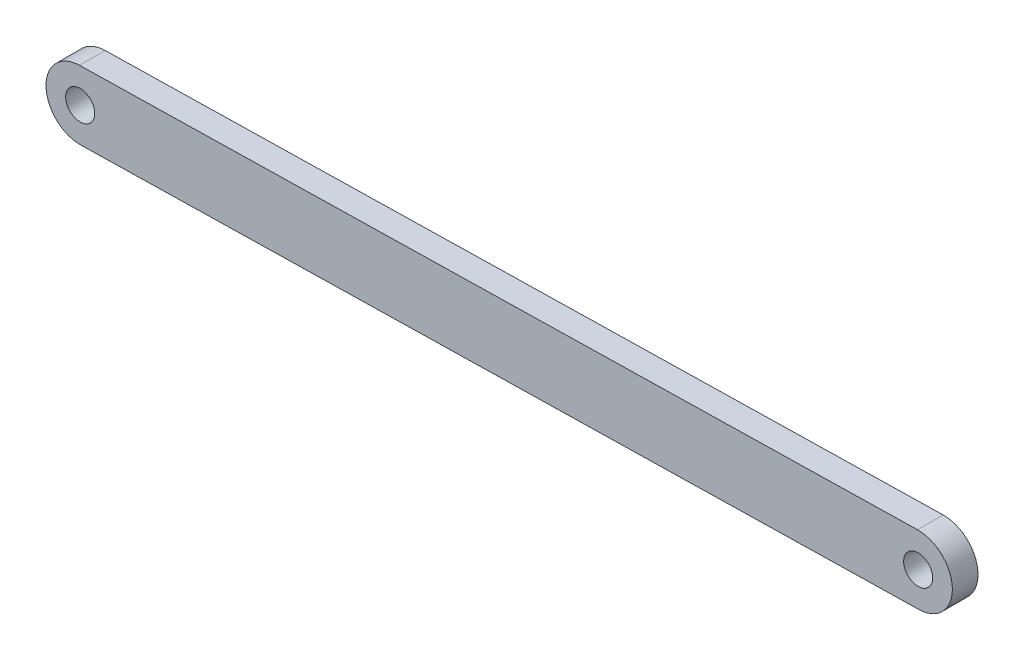
SolidWorks part; units mm, degrees
ref_plane "Front Plane" through (0, 0, 0) normal (0, 0, 1) x (1, 0, 0)
ref_plane "Top Plane" through (0, 0, 0) normal (0, 1, 0) x (1, 0, 0)
ref_plane "Right Plane" through (0, 0, 0) normal (1, 0, 0) x (0, 0, -1)
sketch "Sketch1" plane through (0, 0, 0) normal (0, 0, 1) x (1, 0, 0)
  line L0 (-12.0813, 0.8486) -> (85.9167, 2.8126) construction
  line L1 (-12.0813, 0.8486) -> (85.9167, 2.8126) construction
  line L2 (-12.1615, 4.8478) -> (85.8366, 6.8118)
  line L3 (-12.0012, -3.1505) -> (85.9969, -1.1866)
  circle A0 centre (-12.0813, 0.8486) radius 1.7
  circle A1 centre (85.9167, 2.8126) radius 1.7
  arc A2 (-12.1615, 4.8478) -> (-12.0012, -3.1505) centre (-12.0813, 0.8486) ccw
  arc A3 (85.9969, -1.1866) -> (85.8366, 6.8118) centre (85.9167, 2.8126) ccw
  circle A4 centre (-12.0813, 0.8486) radius 1.65 construction
  circle A5 centre (85.9167, 2.8126) radius 1.65 construction
  point P1 (36.9177, 1.8306)
  point P12 (0, 0)
  dimension "D1" = 3.4
  dimension "D3" = 8
extrude "Boss-Extrude1" add sketch "Sketch1" along normal blind 3
